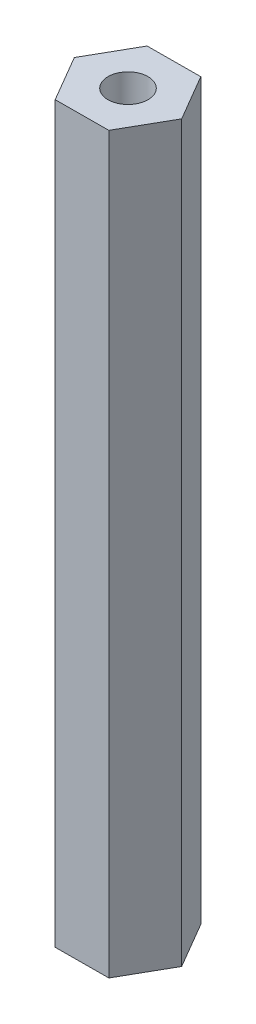
SolidWorks part; units mm, degrees
ref_plane "Front Plane" through (0, 0, 0) normal (0, 0, 1) x (1, 0, 0)
ref_plane "Top Plane" through (0, 0, 0) normal (0, 1, 0) x (1, 0, 0)
ref_plane "Right Plane" through (0, 0, 0) normal (1, 0, 0) x (0, 0, -1)
sketch "Sketch1" plane through (0, 0, 0) normal (0, 1, 0) x (1, 0, 0)
  line L1 (-1.9811, -3.475) -> (2.0189, -3.4531)
  line L2 (2.0189, -3.4531) -> (3.9999, 0.0218)
  line L3 (3.9999, 0.0218) -> (1.9811, 3.475)
  line L4 (1.9811, 3.475) -> (-2.0189, 3.4531)
  line L5 (-2.0189, 3.4531) -> (-3.9999, -0.0218)
  line L6 (-3.9999, -0.0218) -> (-1.9811, -3.475)
  circle A0 centre (0, 0) radius 1.5
  circle A2 centre (0, 0) radius 4 construction
  dimension "D1" = 3
extrude "Boss-Extrude1" add sketch "Sketch1" along normal blind 55
